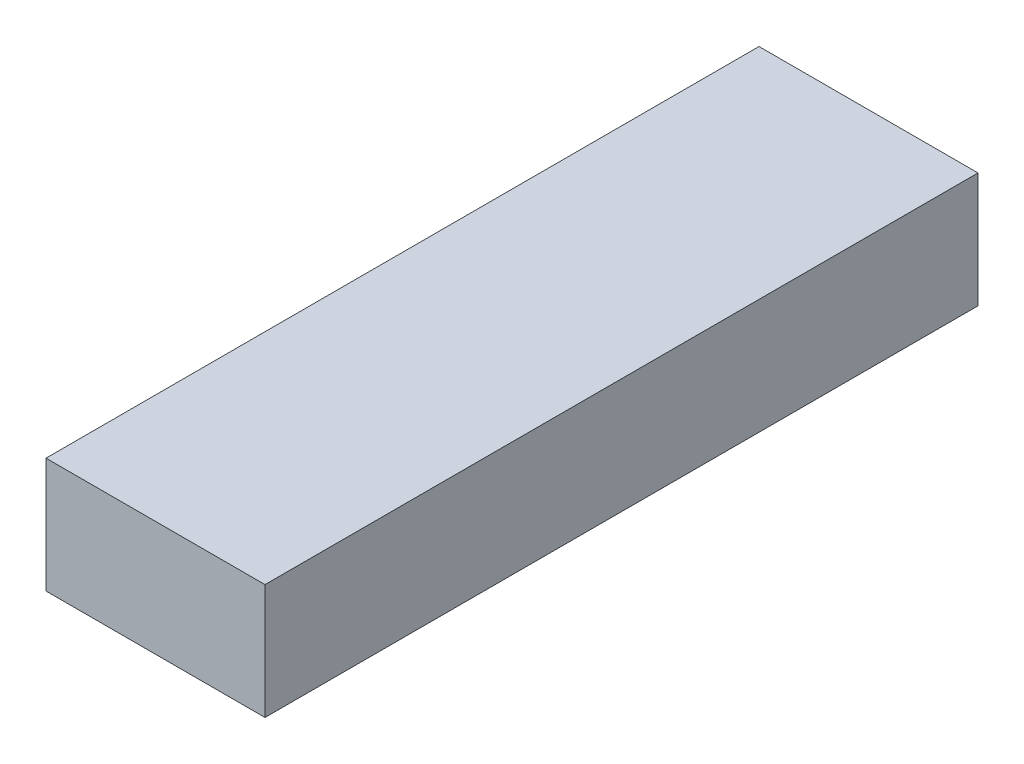
SolidWorks part; units mm, degrees
ref_plane "前视基准面" through (0, 0, 0) normal (0, 0, 1) x (1, 0, 0)
ref_plane "上视基准面" through (0, 0, 0) normal (0, 1, 0) x (1, 0, 0)
ref_plane "右视基准面" through (0, 0, 0) normal (1, 0, 0) x (0, 0, -1)
other "Configuration Table"
sketch "草图1" plane through (0, 0, 0) normal (0, 1, 0) x (1, 0, 0)
  line L1 (-21.5, -70) -> (21.5, -70)
  line L2 (-21.5, -70) -> (-21.5, 70)
  line L3 (-21.5, 70) -> (21.5, 70)
  line L4 (21.5, -70) -> (21.5, 70)
  line L5 (-21.5, -70) -> (21.5, 70) construction
  line L6 (-21.5, 70) -> (21.5, -70) construction
  point P0 (0, 0)
  dimension "D1" = 43
  dimension "D2" = 140
extrude "凸台-拉伸1" add sketch "草图1" along normal blind 22.6
